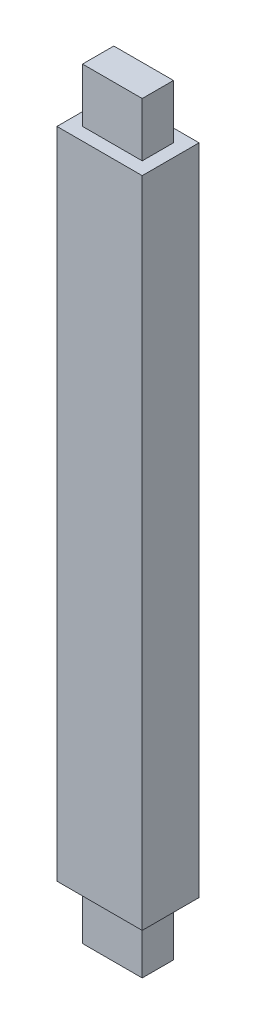
SolidWorks part; units mm, degrees
ref_plane "Front Plane" through (0, 0, 0) normal (0, 0, 1) x (1, 0, 0)
ref_plane "Top Plane" through (0, 0, 0) normal (0, 1, 0) x (1, 0, 0)
ref_plane "Right Plane" through (0, 0, 0) normal (1, 0, 0) x (0, 0, -1)
sketch "Sketch1" plane through (0, 0, 0) normal (0, 1, 0) x (1, 0, 0)
  line L1 (-7.5, 5) -> (7.5, 5)
  line L2 (-7.5, 5) -> (-7.5, -5)
  line L3 (-7.5, -5) -> (7.5, -5)
  line L4 (7.5, 5) -> (7.5, -5)
  line L5 (-7.5, 5) -> (7.5, -5) construction
  line L6 (-7.5, -5) -> (7.5, 5) construction
  point P0 (0, 0)
  dimension "D1" = 15
  dimension "D2" = 10
extrude "Boss-Extrude1" add sketch "Sketch1" along normal mid plane 115
sketch "Sketch2" plane through (0, 57.5, 0) normal (0, 1, 0) x (1, 0, 0)
  line L8 (5.25, -2.75) -> (5.25, 2.75)
  line L9 (5.25, 2.75) -> (-5.25, 2.75)
  line L10 (-5.25, 2.75) -> (-5.25, -2.75)
  line L11 (-5.25, -2.75) -> (5.25, -2.75)
  line L12 (5.25, -2.75) -> (5.25, 2.75)
  line L13 (5.25, 2.75) -> (-5.25, 2.75)
  line L14 (-5.25, 2.75) -> (-5.25, -2.75)
  line L15 (-5.25, -2.75) -> (5.25, -2.75)
  dimension "D1" = 2.25
extrude "Boss-Extrude2" add sketch "Sketch2" along normal blind 9.5
mirror "Mirror1" about plane through (0, 0, 0) normal (0, 1, 0) of "Boss-Extrude2"
